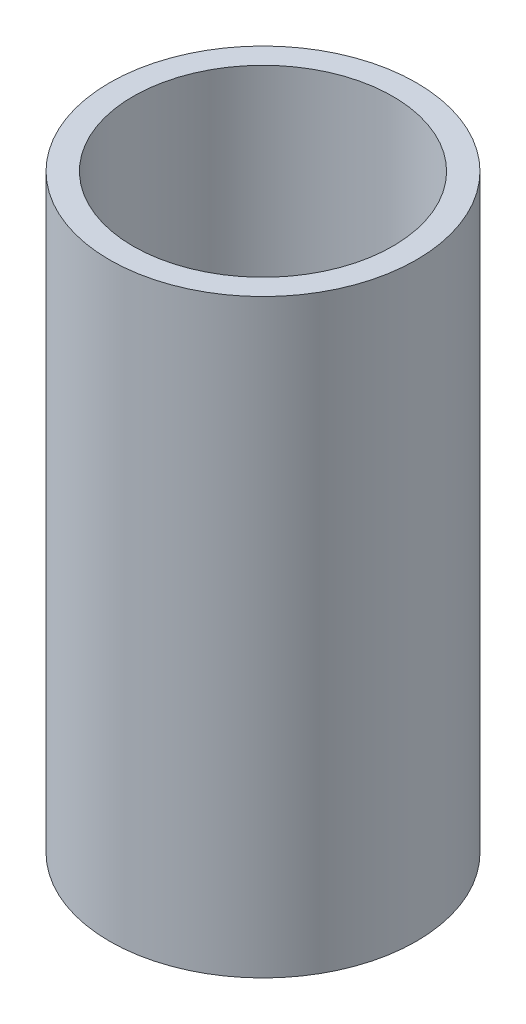
SolidWorks part; units mm, degrees
ref_plane "Ebene vorne" through (0, 0, 0) normal (0, 0, 1) x (1, 0, 0)
ref_plane "Ebene oben" through (0, 0, 0) normal (0, 1, 0) x (1, 0, 0)
ref_plane "Ebene rechts" through (0, 0, 0) normal (1, 0, 0) x (0, 0, -1)
sketch "Sketch1" plane through (0, 0, 0) normal (0, 1, 0) x (1, 0, 0)
  circle A0 centre (0, 0) radius 2.2
  circle A1 centre (0, 0) radius 2.6
  dimension "D1" = 0.4
  dimension "D2" = 5.2
extrude "Boss-Extrude1" add sketch "Sketch1" along normal blind 10
